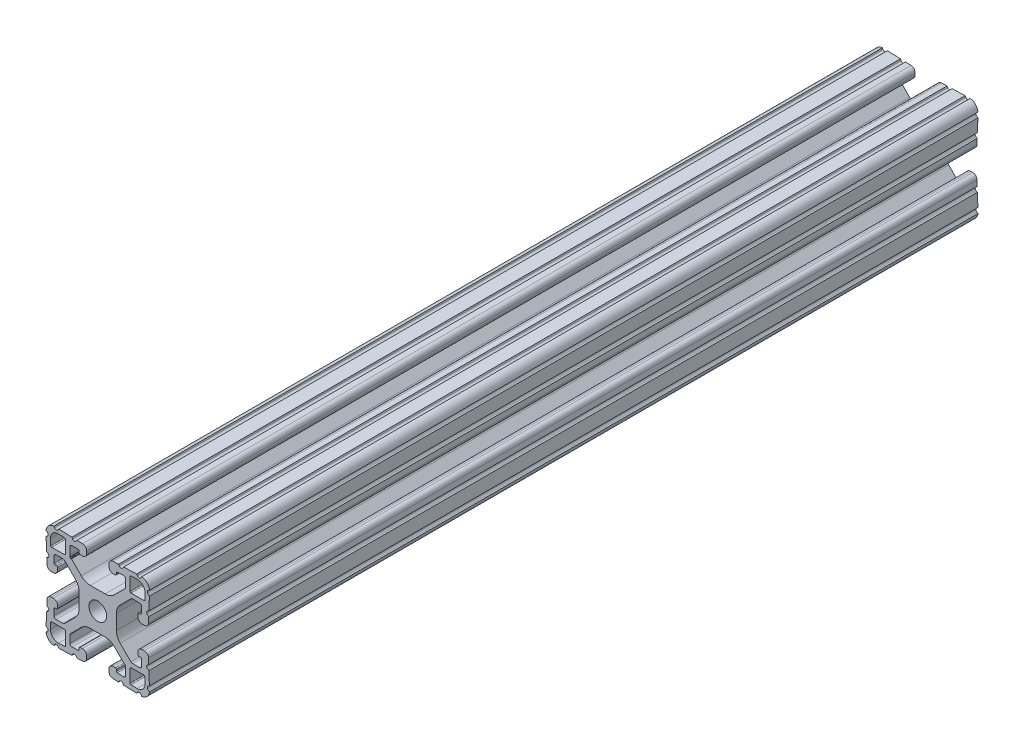
SolidWorks part; units mm, degrees
ref_plane "Front Plane" through (0, 0, 0) normal (0, 0, 1) x (1, 0, 0)
ref_plane "Top Plane" through (0, 0, 0) normal (0, 1, 0) x (1, 0, 0)
ref_plane "Right Plane" through (0, 0, 0) normal (1, 0, 0) x (0, 0, -1)
sketch "Sketch2" plane through (0, 0, 0) normal (0, 0, 1) x (1, 0, 0)
  line L0 (0, 19.05) -> (0, -19.05) construction
  line L1 (-19.05, 0) -> (19.05, 0) construction
  line L2 (4.064, -19.05) -> (19.05, -19.05) construction
  line L3 (19.05, -19.05) -> (19.05, -4.064) construction
  line L4 (4.064, -19.05) -> (4.064, -15.8768) construction
  line L5 (4.064, -15.8768) -> (13.7215, -15.8768) construction
  line L6 (13.7215, -15.8768) -> (4.7027, -6.858) construction
  line L7 (0, 0) -> (19.05, -19.05) construction
  line L8 (19.05, -4.064) -> (15.8768, -4.064) construction
  line L9 (15.8768, -4.064) -> (15.8768, -13.7215) construction
  line L10 (15.8768, -13.7215) -> (6.858, -4.7027) construction
  line L11 (11.3674, -9.2121) -> (9.2121, -11.3674) construction
  line L12 (10.287, -12.4423) -> (10.287, -15.8768) construction
  line L13 (15.7642, -19.0481) -> (4.064, -18.6395) construction
  line L14 (4.064, -18.6395) -> (4.2014, -14.7049) construction
  line L15 (4.2014, -14.7049) -> (6.858, -14.7977) construction
  line L16 (6.858, -14.7977) -> (6.858, -15.8768) construction
  line L17 (19.05, 4.064) -> (19.05, -4.064) construction
  line L18 (-19.05, -19.05) -> (19.05, -19.05) construction
  line L19 (-19.05, -19.05) -> (-19.05, 19.05) construction
  line L20 (-19.05, 19.05) -> (19.05, 19.05) construction
  line L21 (19.05, -19.05) -> (19.05, 19.05) construction
  line L22 (8.5725, -18.7969) -> (8.6004, -17.9973) construction
  line L23 (15.24, -19.0298) -> (15.2679, -18.2301) construction
  circle A0 centre (0, 0) radius 3.2639 construction
  arc A1 (18.1201, -18.1201) -> (15.7642, -19.0481) centre (15.875, -15.875) cw construction
  point P8 (0, -6.858)
  point P16 (10.2898, -10.2898)
  point P28 (11.8872, -11.8872)
  point P34 (8.5725, -18.7969)
  point P36 (15.24, -19.0298)
  point P38 (19.05, 0)
  dimension "D7" = 1.6002
  dimension "Center Hole Diameter" = 6.5278
  dimension "Corner Radius" = 3.175
  dimension "Slot Depth" = 12.192
  dimension "D1" = 3.048
  dimension "D3" = 2
  dimension "Flange Thickness" = 3.937
  dimension "D4" = 3.1732
  dimension "D2" = 20.574
  dimension "D5" = 13.716
  dimension "D6" = 7.1628
  dimension "D8" = 15.24
  dimension "D9" = 8.5725
  dimension "D10" = 0.8001
  dimension "Rail Height" = 38.1
  dimension "Rail Width" = 38.1
  dimension "T Slot Width" = 8.128
sketch "Sketch3" plane through (0, 0, 0) normal (1, 0, 0) x (0, 0, -1)
  line L0 (-152.4, 19.05) -> (152.4, 19.05) construction
  line L1 (-101.6, 0) -> (101.6, 0) construction
  dimension "Length" = 304.8
  dimension "D1" = 50.8
sketch "Sketch4" plane through (0, 0, 0) normal (0, 0, 1) x (1, 0, 0)
  line L1 (6.858, -14.7977) -> (6.858, -15.8768) construction
  line L2 (11.8872, -12.2682) -> (11.8872, -16.9436)
  line L3 (12.2549, -17.3243) -> (14.4454, -17.4008)
  line L7 (12.2682, -11.8872) -> (16.9436, -11.8872)
  line L9 (17.3243, -12.2549) -> (17.4008, -14.4454)
  line L22 (0, 0) -> (19.05, -19.05) construction
  line L23 (15.7642, -19.0481) -> (5.5961, -18.693)
  line L24 (4.064, -17.1065) -> (4.064, -16.344)
  line L25 (5.7069, -14.7575) -> (6.4903, -14.7848)
  line L26 (6.858, -15.1656) -> (6.858, -15.6891)
  line L27 (7.2257, -16.0699) -> (9.4655, -16.1481)
  line L28 (10.287, -15.3549) -> (10.287, -12.771)
  line L29 (10.0545, -12.2098) -> (6.0939, -8.2492)
  line L30 (2.7353, -6.858) -> (0, -6.858)
  line L31 (13.7215, -15.8768) -> (4.7027, -6.858) construction
  line L32 (4.064, -19.05) -> (19.05, -19.05) construction
  line L33 (4.064, -19.05) -> (4.064, -15.8768) construction
  line L34 (0, 19.05) -> (0, -19.05) construction
  line L35 (0, -3.2639) -> (0, -6.858)
  line L36 (0, 0) -> (19.1669, -19.1669) construction
  line L46 (10.287, -12.4423) -> (10.287, -15.8768) construction
  line L47 (6.858, -2.7353) -> (6.858, 0)
  line L48 (12.2098, -10.0545) -> (8.2492, -6.0939)
  line L49 (15.3549, -10.287) -> (12.771, -10.287)
  line L50 (16.0699, -7.2257) -> (16.1481, -9.4655)
  line L51 (15.1656, -6.858) -> (15.6891, -6.858)
  line L52 (14.7575, -5.7069) -> (14.7848, -6.4903)
  line L53 (17.1065, -4.064) -> (16.344, -4.064)
  line L54 (19.0481, -15.7642) -> (18.693, -5.5961)
  line L55 (3.2639, 0) -> (6.858, 0)
  arc A1 (14.4454, -17.4008) -> (17.4008, -14.4454) centre (14.5451, -14.5451) ccw
  arc A10 (16.9436, -11.8872) -> (17.3243, -12.2549) centre (16.9436, -12.2682) cw
  arc A12 (19.0481, -15.7642) -> (15.7642, -19.0481) centre (15.875, -15.875) cw
  arc A13 (3.2639, 0) -> (0, -3.2639) centre (0, 0) cw
  circle A14 centre (0, 0) radius 3.2639 construction
  arc A16 (6.0939, -8.2492) -> (2.7353, -6.858) centre (2.7353, -11.6078) ccw
  arc A17 (5.5961, -18.693) -> (4.064, -17.1065) centre (5.6515, -17.1065) cw
  arc A18 (4.064, -16.344) -> (5.7069, -14.7575) centre (5.6515, -16.344) cw
  arc A19 (9.4655, -16.1481) -> (10.287, -15.3549) centre (9.4933, -15.3549) ccw
  arc A20 (10.287, -12.771) -> (10.0545, -12.2098) centre (9.4933, -12.771) ccw
  arc A21 (6.4903, -14.7848) -> (6.858, -15.1656) centre (6.477, -15.1656) cw
  arc A22 (6.858, -15.6891) -> (7.2257, -16.0699) centre (7.239, -15.6891) ccw
  arc A23 (15.6891, -6.858) -> (16.0699, -7.2257) centre (15.6891, -7.239) cw
  arc A24 (14.7848, -6.4903) -> (15.1656, -6.858) centre (15.1656, -6.477) ccw
  arc A25 (12.771, -10.287) -> (12.2098, -10.0545) centre (12.771, -9.4933) cw
  arc A26 (16.1481, -9.4655) -> (15.3549, -10.287) centre (15.3549, -9.4933) cw
  arc A27 (16.344, -4.064) -> (14.7575, -5.7069) centre (16.344, -5.6515) ccw
  arc A28 (18.693, -5.5961) -> (17.1065, -4.064) centre (17.1065, -5.6515) ccw
  arc A29 (8.2492, -6.0939) -> (6.858, -2.7353) centre (11.6078, -2.7353) cw
  arc A30 (15.7642, -19.0481) -> (18.1201, -18.1201) centre (15.875, -15.875) ccw construction
  arc A31 (11.8872, -12.2682) -> (12.2682, -11.8872) centre (12.2682, -12.2682) cw
  arc A32 (11.8872, -16.9436) -> (12.2549, -17.3243) centre (12.2682, -16.9436) ccw
  point P33 (4.064, -18.6395)
  point P42 (6.858, -4.7027)
  point P45 (4.7027, -6.858)
  point P76 (18.6395, -4.064)
  point P89 (11.8872, -11.8872)
  dimension "D2" = 4.7498
  dimension "D3" = 0.7937
  dimension "D5" = 0.381
  dimension "D6" = 1.5875
  dimension "D8" = 2.8575
  dimension "D1" = 2
  dimension "D4" = 2.6784
  dimension "D7" = 1.6002
extrude "Boss-Extrude1" add sketch "Sketch4" along normal mid plane 304.8
sketch "Sketch8" plane through (0, 0, 0) normal (0, 0, 1) x (1, 0, 0)
  line L0 (7.6492, -18.7647) -> (9.4958, -18.8292)
  line L1 (15.7642, -19.0481) -> (4.064, -18.6395) construction
  line L2 (9.4958, -18.8292) -> (9.2789, -18.4213)
  line L3 (7.894, -18.3729) -> (7.6492, -18.7647)
  line L4 (8.5725, -18.7969) -> (8.6004, -17.9973) construction
  line L5 (14.3167, -18.9975) -> (16.1633, -19.062)
  line L7 (16.1633, -19.062) -> (15.9464, -18.6541)
  line L8 (14.5615, -18.6058) -> (14.3167, -18.9975)
  line L9 (15.24, -19.0298) -> (15.2679, -18.2301) construction
  line L10 (0, 0) -> (19.05, -19.05) construction
  line L11 (18.6058, -14.5615) -> (18.9975, -14.3167)
  line L12 (19.062, -16.1633) -> (18.6541, -15.9464)
  line L13 (18.9975, -14.3167) -> (19.062, -16.1633)
  line L14 (18.3729, -7.894) -> (18.7647, -7.6492)
  line L15 (18.8292, -9.4958) -> (18.4213, -9.2789)
  line L16 (18.7647, -7.6492) -> (18.8292, -9.4958)
  arc A0 (9.2789, -18.4213) -> (7.894, -18.3729) centre (8.5725, -18.7969) ccw
  arc A1 (15.9464, -18.6541) -> (14.5615, -18.6058) centre (15.24, -19.0298) ccw
  arc A2 (18.6541, -15.9464) -> (18.6058, -14.5615) centre (19.0298, -15.24) cw
  arc A3 (18.4213, -9.2789) -> (18.3729, -7.894) centre (18.7969, -8.5725) cw
  dimension "D1" = 60
extrude "Cut-Extrude2" cut sketch "Sketch8" against normal through all both and the other way through all
mirror "Mirror1" about plane through (0, 0, 0) normal (1, 0, 0) of bodies 142 134
mirror "Mirror2" about plane through (0, 0, 0) normal (0, 1, 0) of bodies 135
sketch "Sketch5" plane through (0, 0, 0) normal (0, 0, 1) x (1, 0, 0)
  line L0 (-6.0939, 8.2492) -> (-10.0545, 12.2098) construction
  line L1 (-10.1338, 12.508) -> (-10.1338, 12)
  line L2 (-9.9645, 11.8306) -> (-9.6506, 11.8306)
  line L3 (-9.6506, 11.8306) -> (-9.6506, 12.508)
  line L4 (-9.6506, 12.508) -> (-10.1338, 12.508)
  line L5 (-9.9046, 12.0598) -> (-9.9645, 12) construction
  circle A0 centre (-9.9046, 12.0598) radius 0.254 construction
  arc A1 (-10.287, 12.771) -> (-10.0545, 12.2098) centre (-9.4933, 12.771) ccw construction
  arc A2 (-10.1338, 12) -> (-9.9645, 11.8306) centre (-9.9645, 12) ccw
  dimension "D2" = 0.508
  dimension "D3" = 0.1693
  dimension "D1" = 0.7112
  dimension "D4" = 0.508
extrude "Cut-Extrude1" cut sketch "Sketch5" against normal through all both and the other way through all
ref_plane "Plane1" through (0, 19.05, 0) normal (0, 1, 0) x (-1, 0, 0)
ref_plane "Plane2" through (19.05, 0, 0) normal (1, 0, 0) x (0, 0, -1)
ref_plane "Plane3" through (0, -19.05, 0) normal (0, -1, 0) x (1, 0, 0)
ref_plane "Plane4" through (-19.05, 0, 0) normal (-1, 0, 0) x (0, 0, 1)
equation "\"D1@Boss-Extrude1\"=\"Length@Sketch3\""
equation "\"D6@Sketch4\"=\"Corner Radius@Sketch2\"/2"
equation "\"D3@Sketch4\"=\"D6@Sketch4\"/2"
equation "\"D4@Sketch2\"=\"Flange Thickness@Sketch2\"*.806"
equation "\"D7@Sketch4\"=\"D7@Sketch2\""
equation "\"D8@Sketch4\"=\"Corner Radius@Sketch2\"*.9"
equation "\"D3@Sketch5\"=\"D2@Sketch5\"/3"
equation "\"D4@Sketch5\"=\"D2@Sketch5\""
equation "\"D8@Sketch2\"=\"Rail Width@Sketch2\"*.4"
equation "\"D9@Sketch2\"=\"Rail Width@Sketch2\"*.225"
equation "\"D10@Sketch2\"=\"D7@Sketch2\"/2"
